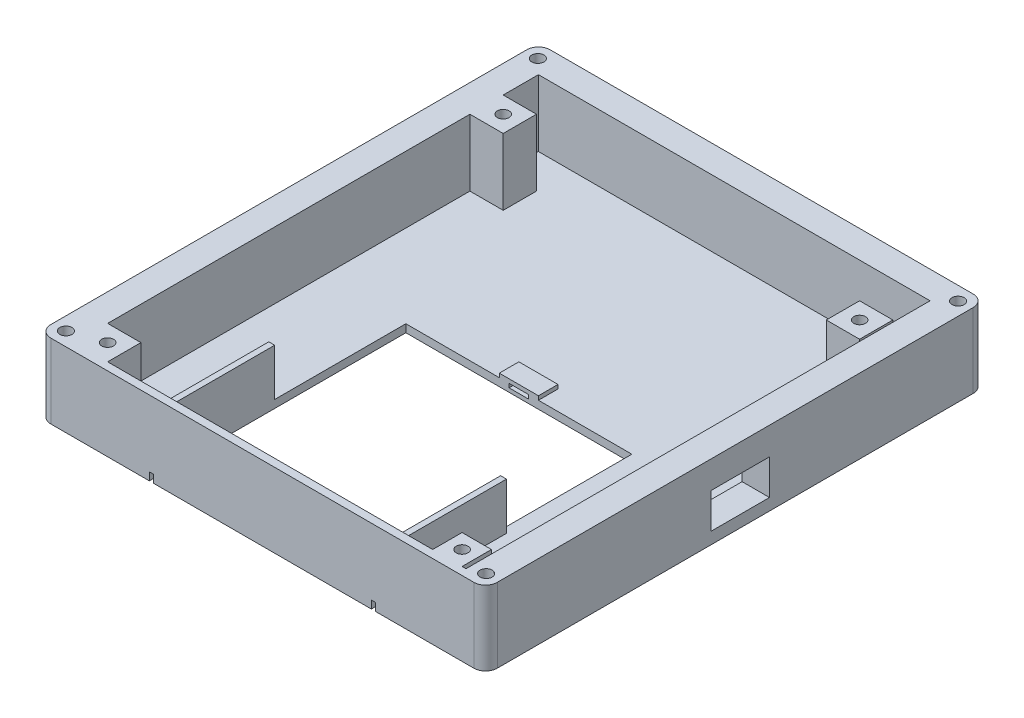
SolidWorks part; units mm, degrees
ref_plane "Front Plane" through (0, 0, 0) normal (0, 0, 1) x (1, 0, 0)
ref_plane "Top Plane" through (0, 0, 0) normal (0, 1, 0) x (1, 0, 0)
ref_plane "Right Plane" through (0, 0, 0) normal (1, 0, 0) x (0, 0, -1)
sketch "Croquis5" plane through (0, 0, 0) normal (0, 0, 1) x (1, 0, 0)
  line L16 (0, 0) -> (39, 0)
  line L17 (0, 0) -> (0, -10)
  line L18 (39, 0) -> (39, -10)
  line L19 (0, -10) -> (-35.5, -10)
  line L20 (-35.5, -10) -> (-35.5, -19)
  line L21 (39, -10) -> (66.5, -10)
  line L22 (66.5, -10) -> (66.5, -19)
  line L24 (-35.5, -19) -> (-36.5, -19)
  line L25 (-36.5, -19) -> (-36.5, -36)
  line L26 (66.5, -19) -> (67.5, -19)
  line L27 (67.5, -19) -> (67.5, -36)
  line L28 (67.5, -36) -> (-36.5, -36)
  dimension "D6" = 27.5
  dimension "D1" = 39
  dimension "D2" = 10
  dimension "D3" = 10
  dimension "D4" = 35.5
  dimension "D5" = 9
  dimension "D7" = 9
  dimension "D8" = 1
  dimension "D9" = 17
  dimension "D10" = 1
  dimension "D11" = 17
extrude "Saliente-Extruir4" add sketch "Croquis5" against normal blind 2
sketch "Croquis7" plane through (0, 0, -2) normal (0, 0, -1) x (-1, 0, 0)
  line L0 (-67.5, -36) -> (-65.5, -36)
  line L1 (36.5, -36) -> (-67.5, -36) construction
  line L2 (-65.5, -36) -> (-65.5, -11.5)
  line L3 (-65.5, -11.5) -> (-66.5, -11.5)
  line L4 (-66.5, -19) -> (-66.5, -10) construction
  line L5 (-66.5, -11.5) -> (-66.5, -19)
  line L6 (-66.5, -19) -> (-67.5, -19)
  line L7 (-67.5, -19) -> (-67.5, -36)
  line L8 (36.5, -36) -> (34.5, -36)
  line L9 (34.5, -36) -> (34.5, -11.5)
  line L10 (34.5, -11.5) -> (35.5, -11.5)
  line L11 (35.5, -10) -> (35.5, -19) construction
  line L12 (35.5, -11.5) -> (35.5, -19)
  line L13 (35.5, -19) -> (36.5, -19)
  line L14 (36.5, -19) -> (36.5, -36)
  dimension "D3" = 2
  dimension "D1" = 2
  dimension "D2" = 24.5
  dimension "D4" = 24.5
extrude "Saliente-Extruir6" add sketch "Croquis7" along normal blind 120.5
sketch "Croquis8" plane through (0, -36, 0) normal (0, -1, 0) x (1, 0, 0)
  line L0 (67.5, -122.5) -> (-36.5, -122.5)
  line L1 (-36.5, -122.5) -> (-36.5, 0)
  line L2 (-36.5, 0) -> (67.5, 0)
  line L3 (67.5, 0) -> (67.5, -122.5)
extrude "Saliente-Extruir7" add sketch "Croquis8" along normal blind 2
sketch "Croquis9" plane through (0, 0, -122.5) normal (0, 0, -1) x (-1, 0, 0)
  line L0 (-65.5, -36) -> (34.5, -36)
  line L1 (34.5, -36) -> (-65.5, -36) construction
  line L2 (34.5, -36) -> (-65.5, -36) construction
  line L3 (34.5, -19) -> (-65.5, -19)
  line L4 (-65.5, -19) -> (34.5, -19)
  line L5 (-65.5, -36) -> (-65.5, -11.5) construction
  line L6 (34.5, -19) -> (34.5, -36)
  line L7 (-65.5, -36) -> (-65.5, -19)
  line M7 (34.5, -11.5) -> (34.5, -36)
  line M8 (34.5, -36) -> (-65.5, -36)
  line M9 (-65.5, -36) -> (-65.5, -11.5)
extrude "Saliente-Extruir8" add sketch "Croquis9" against normal blind 2 contours L3 M7 M9 M8
sketch "Croquis13" plane through (0, -36, 0) normal (0, 1, 0) x (1, 0, 0)
  line L0 (0, 2) -> (-35.5, 2) construction
  line L1 (-34.5, 120.5) -> (-34.5, 2) construction
  line L2 (65.5, 122.5) -> (65.5, 2) construction
  line L3 (-34.5, 2) -> (-26, 2)
  line L4 (-34.5, 2) -> (65.5, 2) construction
  line L5 (-26, 2) -> (-26, 10.5)
  line L7 (-34.5, 10.5) -> (-34.5, 2)
  line L8 (-26, 10.5) -> (-34.5, 10.5)
  line L10 (-34.5, 111.5) -> (-26, 111.5)
  line L11 (-34.5, 111.5) -> (-34.5, 103)
  line L12 (-34.5, 103) -> (-26, 103)
  line L13 (-26, 111.5) -> (-26, 103)
  line L14 (-34.5, 111.5) -> (-26, 103) construction
  line L15 (-34.5, 103) -> (-26, 111.5) construction
  line L21 (56.5, 111.5) -> (65, 111.5)
  line L23 (56.5, 111.5) -> (56.5, 103)
  line L24 (57, 9.5) -> (64.5, 9.5)
  line L25 (57, 9.5) -> (57, 2)
  line L26 (57, 2) -> (64.5, 2)
  line L27 (64.5, 9.5) -> (64.5, 2)
  line L28 (57, 9.5) -> (64.5, 2) construction
  line L29 (57, 2) -> (64.5, 9.5) construction
  line L30 (56.5, 103) -> (65, 103)
  line L31 (65, 111.5) -> (65, 103)
  line L32 (56.5, 111.5) -> (65, 103) construction
  line L33 (56.5, 103) -> (65, 111.5) construction
  circle A0 centre (-30.25, 6.25) radius 1.5
  circle A1 centre (60.75, 5.75) radius 1.5
  circle A2 centre (-30.25, 107.25) radius 1.5
  circle A3 centre (60.75, 107.25) radius 1.5
  dimension "D1" = 3
  dimension "D2" = 3
  dimension "D3" = 3
  dimension "D4" = 3
  dimension "D11" = 4.25
  dimension "D5" = 101
  dimension "D6" = 4.25
  dimension "D7" = 4.25
  dimension "D8" = 4.75
  dimension "D9" = 4.25
  dimension "D10" = 8.5
  dimension "D12" = 8.5
  dimension "D13" = 8.5
  dimension "D14" = 3.75
  dimension "D15" = 101.5
extrude "Saliente-Extruir9" add sketch "Croquis13" along normal up to surface (17 mm away) up to face at (-36, -19, -61.25)
sketch "Croquis14" plane through (0, 0, 0) normal (0, 0, 1) x (1, 0, 0)
  line L0 (-36.5, -38) -> (-41.5, -38)
  line L1 (-41.5, -38) -> (-41.5, -10)
  line L2 (-41.5, -10) -> (-36.5, -10)
  line L3 (-36.5, -10) -> (-36.5, -38)
  line L4 (67.5, -38) -> (72.5, -38)
  line L5 (72.5, -38) -> (72.5, -10)
  line L6 (72.5, -10) -> (67.5, -10)
  line L7 (67.5, -10) -> (67.5, -38)
  dimension "D1" = 5
  dimension "D2" = 5
extrude "Saliente-Extruir10" add sketch "Croquis14" against normal up to surface (122.5 mm away) contours L3 L0 L1 L2 | L7 L4 L5 L6 up to face at (15.5, -19.6667, -122.5)
sketch "Croquis15" plane through (-41.5, 0, 0) normal (-1, 0, 0) x (0, 0, 1)
  line L0 (-122.5, -38) -> (-127.5, -38)
  line L1 (-127.5, -38) -> (-127.5, -10)
  line L2 (-127.5, -10) -> (-122.5, -10)
  line L3 (-122.5, -10) -> (-122.5, -38)
  dimension "D1" = 5
extrude "Saliente-Extruir11" add sketch "Croquis15" against normal up to surface (114 mm away) up to face at (72.5, -24, -61.25)
fillet "Redondeo1" radius 3 4 edges at (72.5, -24, -127.5) (-41.5, -24, -127.5) (72.5, -24, 0) (-41.5, -24, 0)
sketch "Croquis17" plane through (0, 0, 0) normal (0, 0, 1) x (1, 0, 0)
  line L0 (-36.5, -19) -> (-41.5, -19)
  line L1 (-41.5, -38) -> (-41.5, -10) construction
  line L2 (-41.5, -19) -> (-41.5, -10)
  line L3 (-41.5, -10) -> (-36.5, -10)
  line L4 (-36.5, -10) -> (-36.5, -19)
  line L5 (67.5, -19) -> (72.5, -19)
  line L6 (72.5, -10) -> (72.5, -38) construction
  line L7 (72.5, -19) -> (72.5, -10)
  line L8 (72.5, -10) -> (67.5, -10)
  line L9 (67.5, -10) -> (67.5, -19)
extrude "Cortar-Extruir1" cut sketch "Croquis17" against normal up to next
sketch "Croquis18" plane through (67.5, 0, 0) normal (1, 0, 0) x (0, 0, -1)
  line L0 (127.5, -19) -> (122.5, -19)
  line L1 (127.5, -19) -> (122.5, -19) construction
  line L2 (124.5, -19) -> (3, -19) construction
  line L3 (122.5, -19) -> (122.5, -10)
  line L4 (122.5, -10) -> (127.5, -10)
  line L5 (127.5, -10) -> (127.5, -19)
extrude "Cortar-Extruir2" cut sketch "Croquis18" against normal up to next
sketch "Croquis19" plane through (0, -19, 0) normal (0, 1, 0) x (1, 0, 0)
  line L0 (-41.5, 124.5) -> (-41.5, 3) construction
  line L1 (-38.5, 127.5) -> (69.5, 127.5) construction
  line L2 (72.5, 124.5) -> (72.5, 3) construction
  line L3 (-35.5, 0) -> (-38.5, 0) construction
  line L4 (69.5, 0) -> (66.5, 0) construction
  circle A0 centre (-38.15, 124) radius 1.55
  circle A1 centre (69.15, 124) radius 1.55
  circle A2 centre (-38.15, 3.5) radius 1.55
  circle A3 centre (69.15, 3.5) radius 1.55
  dimension "D1" = 3.1
  dimension "D4" = 3.1
  dimension "D7" = 3.1
  dimension "D10" = 3.1
  dimension "D2" = 3.35
  dimension "D3" = 3.5
  dimension "D5" = 3.35
  dimension "D6" = 3.5
  dimension "D8" = 3.35
  dimension "D9" = 3.5
  dimension "D11" = 3.35
  dimension "D12" = 3.5
extrude "Cortar-Extruir3" cut sketch "Croquis19" against normal blind 11
sketch "Croquis20" plane through (0, -38, 0) normal (0, -1, 0) x (1, 0, 0)
  line L0 (15.5, 0) -> (15.5, -127.5) construction
  line L1 (69.5, 0) -> (-38.5, 0) construction
  line L2 (69.5, -127.5) -> (-38.5, -127.5) construction
  line L3 (-13.35, -2) -> (44.35, -2)
  line L4 (44.35, -2) -> (44.35, -65.5)
  line L5 (44.35, -65.5) -> (-13.35, -65.5)
  line L6 (-13.35, -65.5) -> (-13.35, -2)
  point P9 (15.5, -2)
  dimension "D1" = 2
  dimension "D2" = 63.5
  dimension "D3" = 57.7
extrude "Cortar-Extruir4" cut sketch "Croquis20" against normal through all
sketch "Croquis22" plane through (0, 0, -2) normal (0, 0, -1) x (-1, 0, 0)
  line L0 (-44.35, -36) -> (-44.35, -24)
  line L1 (-44.35, -24) -> (-45.85, -24)
  line L2 (-45.85, -24) -> (-45.85, -36)
  line L3 (-45.85, -36) -> (-44.35, -36)
  line L4 (13.35, -36) -> (13.35, -24)
  line L5 (13.35, -24) -> (14.85, -24)
  line L6 (14.85, -24) -> (14.85, -36)
  line L7 (26, -36) -> (13.35, -36) construction
  line L8 (14.85, -36) -> (13.35, -36)
  dimension "D1" = 12
  dimension "D2" = 1.5
  dimension "D3" = 12
  dimension "D4" = 1.5
extrude "Saliente-Extruir12" add sketch "Croquis22" along normal blind 30
sketch "Croquis26" plane through (0, -36, 0) normal (0, 1, 0) x (1, 0, 0)
  line L0 (10.5, 65.5) -> (20.5, 65.5)
  line L1 (44.35, 65.5) -> (-13.35, 65.5) construction
  line L2 (20.5, 65.5) -> (20.5, 70.5)
  line L3 (20.5, 70.5) -> (10.5, 70.5)
  line L4 (10.5, 70.5) -> (10.5, 65.5)
  point P5 (15.5, 65.5)
  dimension "D1" = 5
extrude "Saliente-Extruir14" add sketch "Croquis26" along normal blind 1
sketch "Croquis27" plane through (0, 0, -65.5) normal (0, 0, 1) x (1, 0, 0)
  line L0 (13, -36) -> (18, -36)
  line L1 (18, -36) -> (18, -37)
  line L2 (18, -37) -> (13, -37)
  line L3 (13, -37) -> (13, -36)
  line L4 (10.5, -35) -> (10.5, -36) construction
  line L6 (-13.35, -38) -> (44.35, -38) construction
  dimension "D1" = 5
  dimension "D2" = 1
  dimension "D3" = 2.5
  dimension "D4" = 1
extrude "Cortar-Extruir8" cut sketch "Croquis27" against normal blind 3
sketch "Croquis28" plane through (0, 0, 0) normal (0, 0, 1) x (1, 0, 0)
  line L0 (15.5, -38) -> (15.5, -24.0343)
  line L1 (69.5, -38) -> (-38.5, -38) construction
  line L2 (-13.35, -38) -> (15.5, -38)
  line L3 (43.35, -38) -> (43.35, -36)
  line L4 (43.35, -36) -> (44.35, -36)
  line L5 (44.35, -36) -> (44.35, -38)
  line L6 (43.35, -38) -> (44.35, -38)
  line L7 (-12.35, -36) -> (-13.35, -36)
  line L8 (-12.35, -38) -> (-12.35, -36)
  line L9 (-12.35, -38) -> (-13.35, -38)
  line L10 (-13.35, -36) -> (-13.35, -38)
  point P7 (15.5, -38)
  dimension "D3" = 1
  dimension "D1" = 28.85
  dimension "D2" = 2
extrude "Cortar-Extruir9" cut sketch "Croquis28" against normal blind 10 contours L9 L8 L7 L10 | L5 L6 L3 L4
sketch "Croquis29" plane through (0, 0, -127.5) normal (0, 0, -1) x (-1, 0, 0)
  line L0 (-66.5, -19) -> (35.5, -19)
  line L1 (35.5, -19) -> (35.5, -11.5)
  line L2 (35.5, -11.5) -> (-66.5, -11.5)
  line L3 (-66.5, -11.5) -> (-66.5, -19)
extrude "Cortar-Extruir11" cut sketch "Croquis29" against normal up to surface (125.5 mm away) up to face at (19.3, -23.1333, -2)
sketch "Croquis30" plane through (0, 0, 0) normal (0, 0, 1) x (1, 0, 0)
  line L0 (-35.5, -19) -> (66.5, -19)
  line L1 (66.5, -19) -> (66.5, 0)
  line L2 (66.5, 0) -> (-35.5, 0)
  line L3 (-35.5, 0) -> (-35.5, -19)
extrude "Cortar-Extruir12" cut sketch "Croquis30" against normal through all
sketch "Croquis31" plane through (72.5, 0, 0) normal (1, 0, 0) x (0, 0, -1)
  line L0 (124.5, -38) -> (3, -38) construction
  line L1 (57.5, -26) -> (72.5, -26)
  line L2 (57.5, -26) -> (57.5, -35)
  line L3 (57.5, -35) -> (72.5, -35)
  line L4 (72.5, -26) -> (72.5, -35)
  line L5 (57.5, -26) -> (72.5, -35) construction
  line L6 (57.5, -35) -> (72.5, -26) construction
  line L7 (127.5, -19) -> (127.5, -38) construction
  point P0 (65, -30.5)
  dimension "D1" = 9
  dimension "D2" = 15
  dimension "D3" = 3
  dimension "D4" = 55
extrude "Cortar-Extruir13" cut sketch "Croquis31" against normal blind 10
